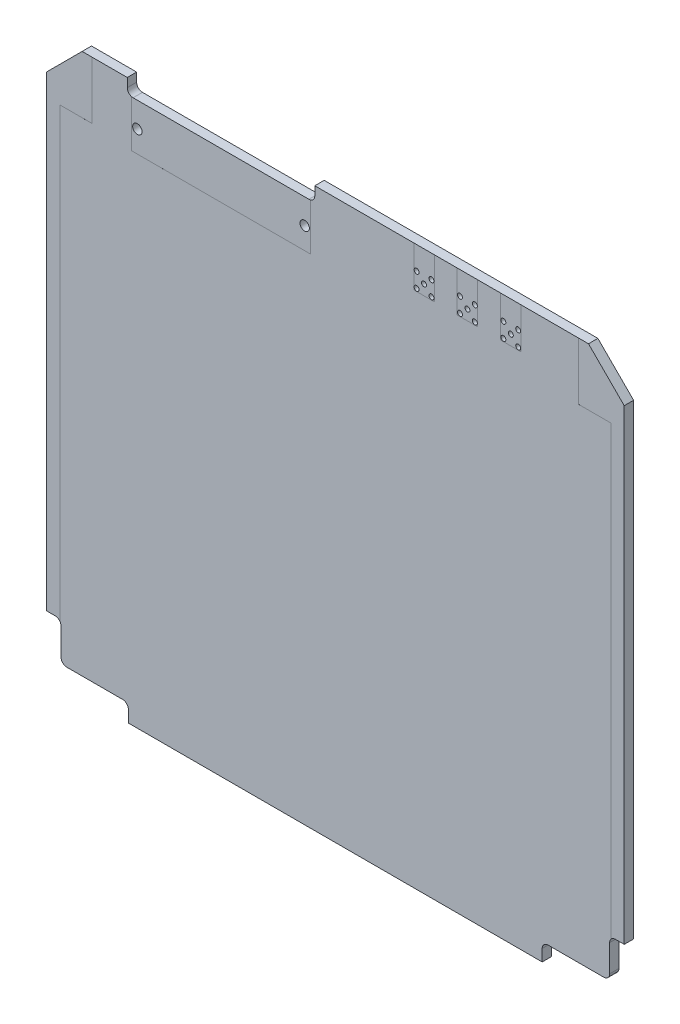
SolidWorks part; units mm, degrees
material "Oshpark board"
ref_plane "Front Plane" through (0, 0, 0) normal (0, 0, 1) x (1, 0, 0)
ref_plane "Top Plane" through (0, 0, 0) normal (0, 1, 0) x (1, 0, 0)
ref_plane "Right Plane" through (0, 0, 0) normal (1, 0, 0) x (0, 0, -1)
ref_plane "Plane4" through (0, 0, -0.0125) normal (0, 0, -1) x (-1, 0, 0)
sketch "Sketch1" plane through (0, 0, -0.0125) normal (0, 0, -1) x (-1, 0, 0)
  line L0 (35.3, -50) -> (35.3, -48)
  line L1 (36.3, -47) -> (45.8, -47)
  line L2 (46.8, -46) -> (46.8, -41.4)
  line L3 (47.8, -40.4) -> (49.3, -40.4)
  line L4 (49.3, -40.4) -> (49.3, 39.2)
  line L5 (49.3, 39.2) -> (43.2, 45.3)
  line L6 (43.2, 45.3) -> (35.5, 45.3)
  line L7 (35.5, 45.3) -> (35.5, 43.8)
  line L8 (34.5, 42.8) -> (4.5, 42.8)
  line L9 (3.5, 43.8) -> (3.5, 45.3)
  line L10 (3.5, 45.3) -> (-43.2, 45.3)
  line L11 (-43.2, 45.3) -> (-49.3, 39.2)
  line L12 (-49.3, 39.2) -> (-49.3, -40.4)
  line L13 (-49.3, -40.4) -> (-47.8, -40.4)
  line L14 (-46.8, -41.4) -> (-46.8, -46)
  line L15 (-45.8, -47) -> (-36.3, -47)
  line L16 (-35.3, -48) -> (-35.3, -50)
  line L17 (-35.3, -50) -> (35.3, -50)
  line L18 (0, -50) -> (0, 45.3) construction
  line L19 (19.5, 42.8) -> (19.5, 25.5258) construction
  line L20 (-13.87, 41.37) -> (-16.41, 38.83) construction
  line L21 (-21.27, 41.37) -> (-23.81, 38.83) construction
  line L22 (-28.67, 41.37) -> (-31.21, 38.83) construction
  arc A0 (35.3, -48) -> (36.3, -47) centre (36.3, -48) cw
  arc A1 (45.8, -47) -> (46.8, -46) centre (45.8, -46) ccw
  arc A2 (46.8, -41.4) -> (47.8, -40.4) centre (47.8, -41.4) cw
  arc A3 (35.5, 43.8) -> (34.5, 42.8) centre (34.5, 43.8) cw
  arc A4 (4.5, 42.8) -> (3.5, 43.8) centre (4.5, 43.8) cw
  arc A5 (-47.8, -40.4) -> (-46.8, -41.4) centre (-47.8, -41.4) cw
  arc A6 (-46.8, -46) -> (-45.8, -47) centre (-45.8, -46) ccw
  arc A7 (-36.3, -47) -> (-35.3, -48) centre (-36.3, -48) cw
  circle A8 centre (-21.27, 41.37) radius 0.425
  circle A9 centre (-23.81, 41.37) radius 0.425
  circle A10 centre (-22.54, 40.1) radius 0.425
  circle A11 centre (-13.87, 41.37) radius 0.425
  circle A12 centre (-23.81, 38.83) radius 0.425
  circle A13 centre (-16.41, 41.37) radius 0.425
  circle A14 centre (-15.14, 40.1) radius 0.425
  circle A15 centre (-21.27, 38.83) radius 0.425
  circle A16 centre (-28.67, 41.37) radius 0.425
  circle A17 centre (-31.21, 41.37) radius 0.425
  circle A18 centre (-16.41, 38.83) radius 0.425
  circle A19 centre (-29.94, 40.1) radius 0.425
  circle A20 centre (-31.21, 38.83) radius 0.425
  circle A21 centre (-28.67, 38.83) radius 0.425
  circle A22 centre (33.775, 38.54) radius 0.8
  circle A23 centre (5.225, 38.54) radius 0.8
  circle A24 centre (-13.87, 38.83) radius 0.425
  point P35 (-15.14, 40.1)
  dimension "D7" = 2.5
  dimension "D8" = 1.6
  dimension "D9" = 14.275
  dimension "D10" = 4.26
  dimension "D11" = 1
  dimension "D12" = 1
  dimension "D13" = 1
  dimension "D14" = 1
  dimension "D15" = 1
  dimension "D16" = 1
  dimension "D17" = 1
  dimension "D18" = 1
  dimension "D26" = 0.85
  dimension "D1" = 98.6
  dimension "D2" = 95.3
  dimension "D3" = 14
  dimension "D4" = 9.6
  dimension "D5" = 2.5
  dimension "D6" = 3
  dimension "D19" = 14
  dimension "D20" = 2.5
  dimension "D21" = 6.1
  dimension "D22" = 6.1
  dimension "D23" = 32
  dimension "D24" = 2.54
  dimension "D25" = 2.54
  dimension "D28" = 7.4
  dimension "D29" = 3.93
  dimension "D30" = 35.43
  dimension "D31" = 45
  dimension "D32" = 45
  dimension "D33" = 29.8
  dimension "D34" = 50
  dimension "D27" = 3
extrude "Boss-Extrude1" add sketch "Sketch1" against normal blind 1.6
sketch "thermalContacts_lower" plane through (0, 0, -0.0125) normal (0, 0, -1) x (-1, 0, 0)
  line L0 (47, 35.5) -> (47, -41.5) construction
  line L1 (41.5, 35.5) -> (41.5, 41.5) construction
  line L2 (41.5, 35.5) -> (47, 35.5) construction
  line L3 (47, 35.5) -> (47, -41.5)
  line L4 (41.5, 35.5) -> (41.5, 41.5)
  line L5 (41.5, 35.5) -> (47, 35.5)
  line L6 (-47, 35.5) -> (-47, -41.5) construction
  line L7 (-41.5, 35.5) -> (-47, 35.5) construction
  line L8 (-41.5, 35.5) -> (-41.5, 41.5) construction
  line L9 (-47, 35.5) -> (-47, -41.5)
  line L10 (-41.5, 35.5) -> (-47, 35.5)
  line L11 (-41.5, 35.5) -> (-41.5, 41.5)
  line L12 (-41.5, 41.5) -> (-41.5, 47) construction
  line L13 (-41.5, 41.5) -> (-49.5, 41.5) construction
  line L14 (-41.5, 41.5) -> (-41.5, 47)
  line L15 (-41.5, 41.5) -> (-49.5, 41.5) construction
  line L16 (41.5, 41.5) -> (41.5, 47) construction
  line L17 (41.5, 41.5) -> (49.5, 41.5) construction
  line L18 (41.5, 41.5) -> (41.5, 47)
  line L19 (41.5, 41.5) -> (49.5, 41.5) construction
  line L20 (47, -41.5) -> (59.8273, -41.5)
  line L21 (59.8273, -41.5) -> (59.8273, 47)
  line L22 (-56.1922, 47) -> (-41.5, 47)
  line L23 (41.5, 47) -> (59.8273, 47)
  line L24 (-56.1922, 47) -> (-56.1922, -41.5)
  line L25 (-47, -41.5) -> (-56.1922, -41.5)
sketch "thermalContacts_upper" plane through (0, 0, 1.5875) normal (0, 0, 1) x (1, 0, 0)
  line L3 (-47, 35.5) -> (-47, -41.5)
  line L4 (-41.5, 35.5) -> (-41.5, 41.5)
  line L5 (-41.5, 35.5) -> (-47, 35.5)
  line L9 (47, 35.5) -> (47, -41.5)
  line L10 (41.5, 35.5) -> (47, 35.5)
  line L11 (41.5, 35.5) -> (41.5, 41.5)
  line L14 (41.5, 41.5) -> (41.5, 47)
  line L15 (41.5, 41.5) -> (49.5, 41.5) construction
  line L18 (-41.5, 41.5) -> (-41.5, 47)
  line L19 (-41.5, 41.5) -> (-49.5, 41.5) construction
  line L20 (47, -41.5) -> (59.8273, -41.5)
  line L21 (59.8273, -41.5) -> (59.8273, 47)
  line L22 (59.8273, 47) -> (41.5, 47)
  line L23 (-41.5, 47) -> (-56.1922, 47)
  line L24 (-56.1922, 47) -> (-56.1922, -41.5)
  line L25 (-56.1922, -41.5) -> (-47, -41.5)
extrude "Cut-Extrude1" cut sketch "thermalContacts_lower" against normal blind 0.0001
extrude "Cut-Extrude2" cut sketch "thermalContacts_upper" against normal blind 0.0001
sketch "partFootprints" plane through (0, 0, 1.5875) normal (0, 0, 1) x (1, 0, 0)
  line L0 (-34.74, 34.84) -> (-34.74, 42.8292)
  line L1 (-4.26, 34.84) -> (-34.74, 34.84)
  line L2 (-41.5, 45.3) -> (-35.5, 45.3) construction
  line L3 (-36.1132, 45.3) -> (-39.5054, 45.3) construction
  line L4 (-4.26, 34.84) -> (-4.26, 42.8292)
  line L5 (-49.3, -40.4) -> (-49.3, 39.2) construction
  line L6 (13.39, 45.3) -> (13.39, 38.35)
  line L7 (13.39, 38.35) -> (16.89, 38.35)
  line L8 (16.89, 38.35) -> (16.89, 45.3)
  line L9 (16.89, 45.3) -> (13.39, 45.3)
  line L10 (20.79, 45.3) -> (20.79, 38.35)
  line L11 (20.79, 38.35) -> (24.29, 38.35)
  line L12 (24.29, 38.35) -> (24.29, 45.3)
  line L13 (24.29, 45.3) -> (20.79, 45.3)
  line L14 (28.19, 45.3) -> (28.19, 38.35)
  line L15 (28.19, 38.35) -> (31.69, 38.35)
  line L16 (31.69, 38.35) -> (31.69, 45.3)
  line L17 (31.69, 45.3) -> (28.19, 45.3)
  line L19 (14.12, 38.35) -> (16.16, 38.35) construction
  line L20 (-34.74, 42.8292) -> (-4.26, 42.8292)
  line L21 (-3.5, 45.3) -> (41.5, 45.3) construction
  line L22 (14.12, 38.35) -> (16.16, 38.35) construction
  line L23 (13.39, 41.85) -> (13.39, 38.35) construction
  line L24 (16.89, 41.85) -> (16.89, 38.35) construction
  line L25 (13.39, 41.85) -> (13.39, 38.35) construction
  line L26 (16.89, 41.85) -> (16.89, 38.35) construction
  arc A0 (-35.5, 43.8) -> (-34.5, 42.8) centre (-34.5, 43.8) ccw construction
  arc A1 (-4.5, 42.8) -> (-3.5, 43.8) centre (-4.5, 43.8) ccw construction
  dimension "D1" = 10.46
  dimension "D2" = 14.56
  dimension "D3" = 30.48
  dimension "D7" = 7.4
  dimension "D6" = 3
extrude "Cut-Extrude3" cut sketch "partFootprints" against normal blind 0.0001
